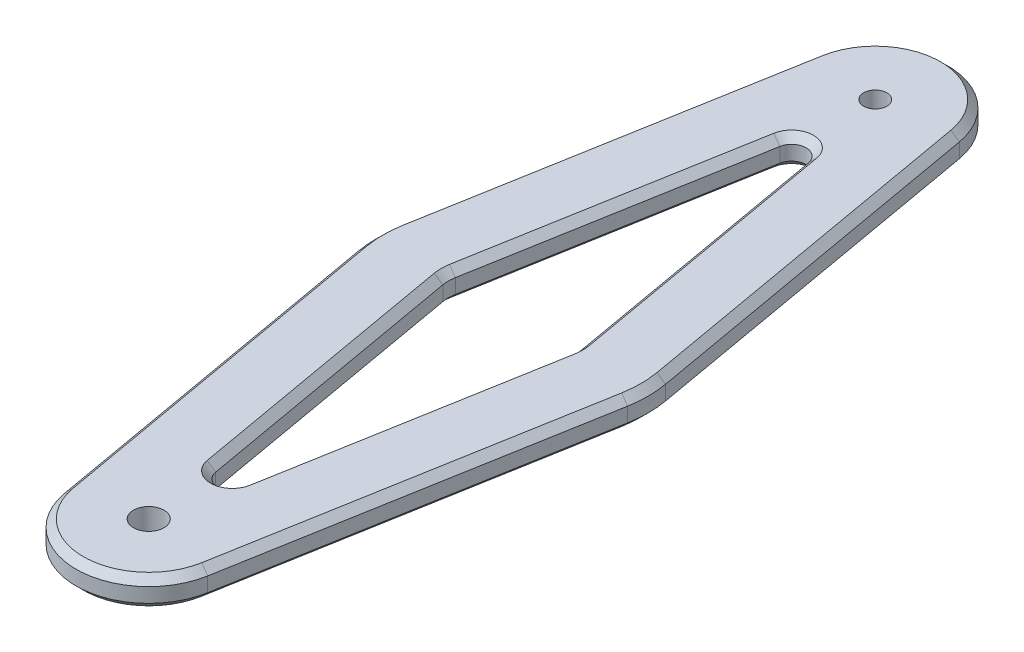
SolidWorks part; units mm, degrees
ref_plane "前视基准面" through (0, 0, 0) normal (0, 0, 1) x (1, 0, 0)
ref_plane "上视基准面" through (0, 0, 0) normal (0, 1, 0) x (1, 0, 0)
ref_plane "右视基准面" through (0, 0, 0) normal (1, 0, 0) x (0, 0, -1)
other "Configuration Table"
sketch "草图1" plane through (0, 0, 0) normal (0, 1, 0) x (1, 0, 0)
  line L0 (0, 0) -> (95.6592, 0) construction
  line L1 (0, 0) -> (0, 50) construction
  line L2 (-18.5113, 2.6047) -> (-9.8481, 51.7365)
  line L3 (18.5113, 2.6047) -> (9.8481, 51.7365)
  line L4 (18.5113, -2.6047) -> (9.8481, -51.7365)
  line L5 (-18.5113, -2.6047) -> (-9.8481, -51.7365)
  arc A0 (-9.8481, 51.7365) -> (9.8481, 51.7365) centre (0, 50) cw
  arc A1 (-9.8481, -51.7365) -> (9.8481, -51.7365) centre (0, -50) ccw
  arc A2 (18.5113, 2.6047) -> (18.5113, -2.6047) centre (3.7392, 0) cw
  arc A3 (-18.5113, 2.6047) -> (-18.5113, -2.6047) centre (-3.7392, 0) ccw
  point P14 (18.9706, 0)
  point P17 (-18.9706, 0)
  dimension "D2" = 50
  dimension "D3" = 10
  dimension "D4" = 15
  dimension "D1" = 80
extrude "凸台-拉伸1" add sketch "草图1" along normal mid plane 4
sketch "草图2" plane through (0, 2, 0) normal (0, 1, 0) x (1, 0, 0)
  circle A0 centre (0, 50) radius 1.6
  circle A1 centre (0, -50) radius 2.1
  dimension "D1" = 4.2
  dimension "D2" = 3.2
extrude "切除-拉伸1" cut sketch "草图2" against normal through all
sketch "草图6" plane through (0, 0, 0) normal (0, 1, 0) x (1, 0, 0)
  line L8 (0, 50) -> (-8.6633, 0.8682)
  line L9 (-8.6633, -0.8682) -> (0, -50)
  line L10 (0, -50) -> (8.6633, -0.8682)
  line L11 (8.6633, 0.8682) -> (0, 50)
  line L12 (-1.9696, 38.8298) -> (-8.6633, 0.8682)
  line L13 (-8.6633, -0.8682) -> (-1.9696, -38.8298)
  line L14 (1.9696, -38.8298) -> (8.6633, -0.8682)
  line L15 (8.6633, 0.8682) -> (1.9696, 38.8298)
  arc A4 (-1.9696, -38.8298) -> (1.9696, -38.8298) centre (0, -38.4825) ccw
  arc A5 (-1.9696, 38.8298) -> (1.9696, 38.8298) centre (0, 38.4825) cw
  arc A6 (-8.6633, 0.8682) -> (-8.6633, -0.8682) centre (-3.7392, 0) ccw
  arc A7 (-8.6633, 0.8682) -> (-8.6633, -0.8682) centre (-3.7392, 0) ccw
  arc A8 (8.6633, -0.8682) -> (8.6633, 0.8682) centre (3.7392, 0) ccw
  arc A9 (8.6633, -0.8682) -> (8.6633, 0.8682) centre (3.7392, 0) ccw
  dimension "D2" = 2
  dimension "D1" = 10
extrude "切除-拉伸4" cut sketch "草图6" against normal through all both and the other way through all
chamfer "倒角1" distance 1 angle 45 32 edges at (-14.1797, 2, -27.1706) (-18.7392, 2, 0) (0, 2, -60) (-14.1797, 2, 27.1706) (14.1797, 2, -27.1706) (0, 2, 60) (18.7392, 2, 0) (14.1797, 2, 27.1706) (-14.1797, -2, 27.1706) (0, -2, 60) (-18.7392, -2, 0) (14.1797, -2, 27.1706) (-14.1797, -2, -27.1706) (18.7392, -2, 0) (0, -2, -60) (14.1797, -2, -27.1706) (-5.3164, -2, 19.849) (-5.3164, -2, -19.849) (0, -2, 40.4825) (0, -2, -40.4825) (5.3164, -2, 19.849) (5.3164, -2, -19.849) (5.3164, 2, 19.849) (5.3164, 2, -19.849) (0, 2, 40.4825) (0, 2, -40.4825) (-5.3164, 2, 19.849) (-5.3164, 2, -19.849) (-8.7392, -2, 0) (8.7392, -2, 0) (8.7392, 2, 0) (-8.7392, 2, 0)
